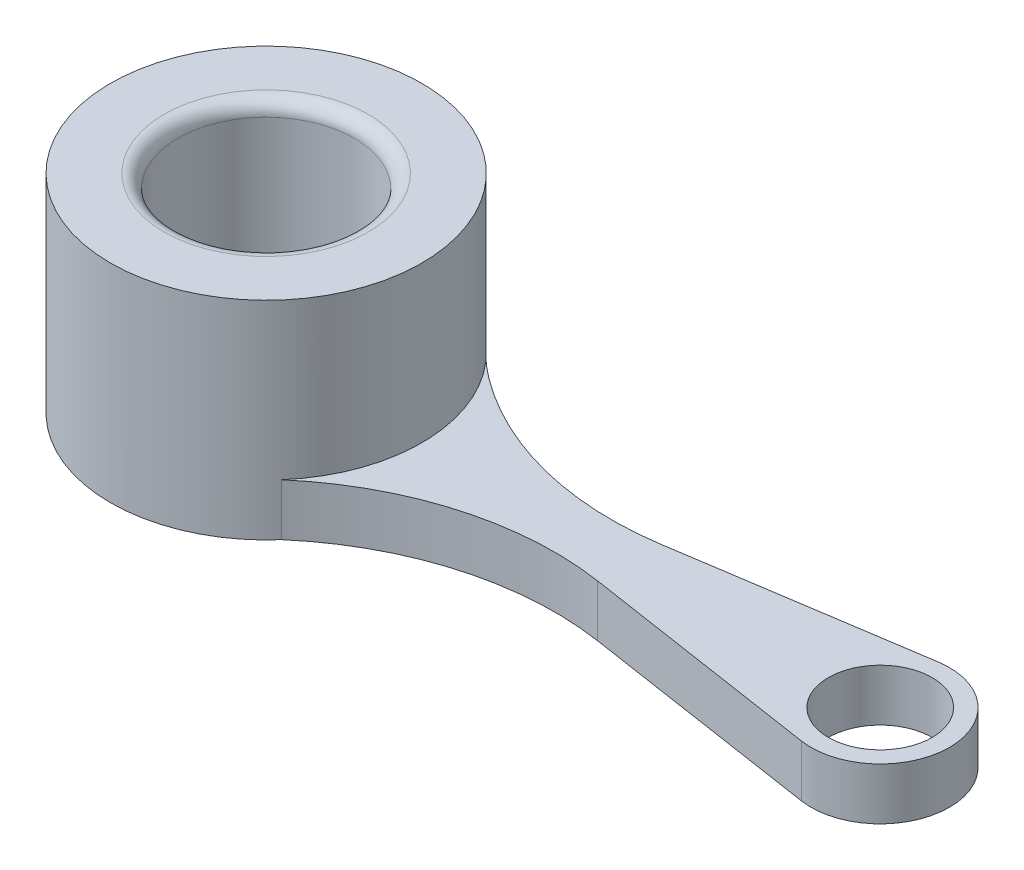
SolidWorks part; units mm, degrees
ref_plane "Front Plane" through (0, 0, 0) normal (0, 0, 1) x (1, 0, 0)
ref_plane "Top Plane" through (0, 0, 0) normal (0, 1, 0) x (1, 0, 0)
ref_plane "Right Plane" through (0, 0, 0) normal (1, 0, 0) x (0, 0, -1)
sketch "Sketch2" plane through (0, 0, 0) normal (0, 1, 0) x (1, 0, 0)
  line L0 (0, 0) -> (25, 0)
  line L1 (25, 0) -> (25, 9)
  line L2 (25, 9) -> (0, 9)
  line L3 (0, 9) -> (0, 0)
  line L4 (0, 4.5) -> (4.5, 4.5) construction
  line L5 (25, 4.5) -> (22.25, 4.5) construction
  dimension "D1" = 25
  dimension "D2" = 9
  dimension "D3" = 4.5
  dimension "D5" = 2.75
extrude "Boss-Extrude3" add sketch "Sketch2" along normal blind 6
sketch "Sketch3" plane through (0, 6, 0) normal (0, 1, 0) x (1, 0, 0)
  line L0 (0, 4.5) -> (4.5, 4.5) construction
  line L1 (0, 9) -> (0, 0) construction
  line L2 (25, 4.5) -> (22.25, 4.5) construction
  line L3 (25, 0) -> (25, 9) construction
  circle A0 centre (4.5, 4.5) radius 2.55
  circle A1 centre (22.25, 4.5) radius 1.75
  dimension "D3" = 5.1
  dimension "D4" = 3.5
  dimension "D1" = 4.5
  dimension "D2" = 2.75
extrude "Cut-Extrude1" cut sketch "Sketch3" against normal blind 5 contours A0
sketch "Sketch4" plane through (0, 6, 0) normal (0, 1, 0) x (1, 0, 0)
  line L0 (25, 4.5) -> (22.25, 4.5) construction
  line L1 (25, 0) -> (25, 9) construction
  circle A0 centre (22.25, 4.5) radius 1.5
  dimension "D2" = 3
  dimension "D1" = 2.75
extrude "Cut-Extrude2" cut sketch "Sketch4" against normal through all both and the other way through all
sketch "Sketch5" plane through (0, 6, 0) normal (0, 1, 0) x (1, 0, 0)
  line L0 (4.5, 9) -> (0, 9)
  line L1 (0, 9) -> (0, 4.5)
  line L2 (0, 4.5) -> (0, 0)
  line L3 (0, 0) -> (4.5, 0)
  line L4 (4.5, 0) -> (25, 0)
  line L5 (25, 0) -> (25, 9)
  line L6 (25, 9) -> (4.5, 9)
  circle A0 centre (4.5, 4.5) radius 4.5
  circle M9 centre (22.25, 4.5) radius 1.5
  line M12 (0, 0) -> (25, 0)
  line M13 (25, 0) -> (25, 9)
  line M14 (25, 9) -> (0, 9)
extrude "Cut-Extrude3" cut sketch "Sketch5" against normal blind 4.5 contours A0 M12 M13 M14 M9
sketch "Sketch6" plane through (0, 6, 0) normal (0, 1, 0) x (1, 0, 0)
  line L0 (4.5, 9) -> (0, 9)
  line L1 (0, 9) -> (0, 0)
  line L2 (0, 0) -> (4.5, 0)
  circle A0 centre (4.5, 4.5) radius 4.5
  line M2 (0, 0) -> (4.5, 0)
  line M4 (4.5, 9) -> (0, 9)
  line M5 (0, 9) -> (0, 0)
extrude "Cut-Extrude4" cut sketch "Sketch6" against normal through all contours A0 M4 M5 | A0 L1 M2
sketch "Sketch7" plane through (0, 6, 0) normal (0, 1, 0) x (1, 0, 0)
  circle A0 centre (4.5, 4.5) radius 2.8
  circle A2 centre (4.5, 4.5) radius 2.6
  dimension "D1" = 5.6
fillet "Fillet2" radius 0.4 1 edges at (4.5, 6, -1.95)
sketch "Sketch8" plane through (0, 0, 0) normal (0, -1, 0) x (1, 0, 0)
  circle A0 centre (4.5, -4.5) radius 1
  dimension "D1" = 2
extrude "Cut-Extrude5" cut sketch "Sketch8" against normal through all
sketch "Sketch9" plane through (0, 1.5, 0) normal (0, 1, 0) x (1, 0, 0)
  line L0 (4.5, 9) -> (25, 9)
  line L1 (25, 9) -> (25, 0)
  line L2 (25, 0) -> (4.5, 0)
  line L3 (9, 4.5) -> (15.2993, 4.5) construction
  line L4 (9, 4.5) -> (25, 6.9431)
  line L5 (9, 4.5) -> (25, 2.0569)
  line L6 (25, 2.0569) -> (25, 6.9431)
  circle A0 centre (22.25, 4.5) radius 2
  arc A1 (4.5, 9) -> (4.5, 0) centre (4.5, 4.5) cw
  arc A2 (15, 5.4162) -> (7.8993, 7.4487) centre (13.6637, 14.1674) cw
  arc A3 (15, 3.5838) -> (7.8993, 1.5513) centre (13.6637, -5.1674) ccw
  dimension "D1" = 4
  dimension "D2" = 6
extrude "Cut-Extrude7" cut sketch "Sketch9" against normal blind 10 contours A2 L4 L1 L6 | L5 A3 A1 L4 | L3 A0 L5 L1 | A0 L3 L6 L4
